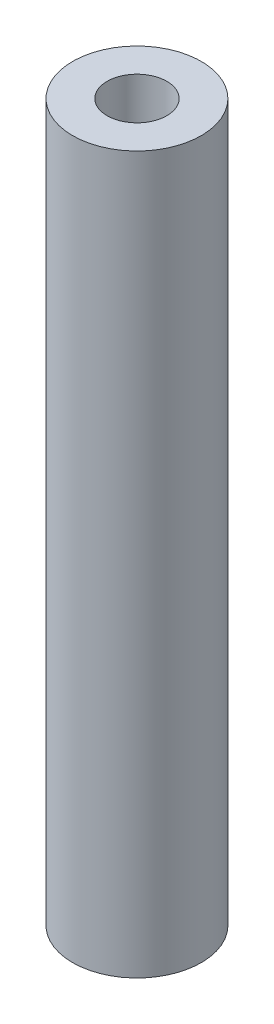
SolidWorks part; units mm, degrees
ref_plane "Front Plane" through (0, 0, 0) normal (0, 0, 1) x (1, 0, 0)
ref_plane "Top Plane" through (0, 0, 0) normal (0, 1, 0) x (1, 0, 0)
ref_plane "Right Plane" through (0, 0, 0) normal (1, 0, 0) x (0, 0, -1)
sketch "Sketch1" plane through (0, 0, 0) normal (0, 1, 0) x (1, 0, 0)
  circle A0 centre (0, 0) radius 1.125
  circle A1 centre (0, 0) radius 2.425
  dimension "D1" = 2.25
  dimension "D2" = 4.85
extrude "Base" add sketch "Sketch1" along normal blind 27
